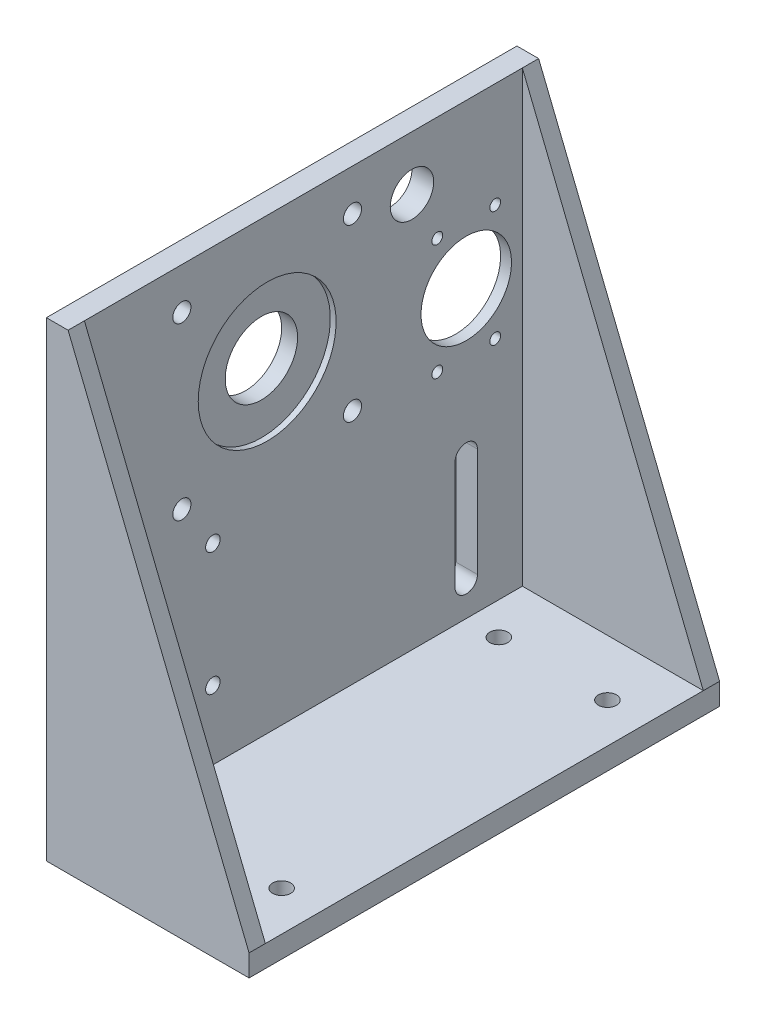
SolidWorks part; units mm, degrees
material "AISI 304"
ref_plane "Front" through (0, 0, 0) normal (0, 0, 1) x (1, 0, 0)
ref_plane "Top" through (0, 0, 0) normal (0, 1, 0) x (1, 0, 0)
ref_plane "Right" through (0, 0, 0) normal (1, 0, 0) x (0, 0, -1)
sketch "Sketch1" plane through (0, 0, 0) normal (1, 0, 0) x (0, 0, -1)
  line L1 (0, 0) -> (130, 0)
  line L2 (0, 0) -> (0, 130)
  line L3 (0, 130) -> (130, 130)
  line L4 (130, 0) -> (130, 130)
  dimension "D1" = 130
  dimension "D2" = 130
extrude "Boss-Extrude1" add sketch "Sketch1" along normal blind 6
sketch "Sketch2" plane through (6, 0, 0) normal (1, 0, 0) x (0, 0, -1)
  line L0 (130, 0) -> (130, 130) construction
  line L1 (0, 0) -> (130, 0)
  line L2 (0, 0) -> (0, 6)
  line L3 (0, 6) -> (130, 6)
  line L4 (130, 0) -> (130, 6)
  dimension "D1" = 6
extrude "Boss-Extrude2" add sketch "Sketch2" along normal blind 50
sketch "Sketch3" plane through (0, 0, -130) normal (0, 0, -1) x (-1, 0, 0)
  line L0 (-6, 130) -> (-56, 6)
  line L1 (-6, 6) -> (-6, 130) construction
  line L2 (-56, 6) -> (-6, 6) construction
  line L3 (-6, 6) -> (-6, 130)
  line L4 (-56, 6) -> (-6, 6)
extrude "Boss-Extrude3" add sketch "Sketch3" against normal blind 4.5
sketch "Sketch4" plane through (0, 0, 0) normal (0, 0, 1) x (1, 0, 0)
  line L0 (6, 130) -> (56, 6)
  line L1 (56, 6) -> (6, 6) construction
  line L2 (6, 130) -> (6, 6) construction
  line L3 (56, 6) -> (6, 6)
  line L4 (6, 130) -> (6, 6)
extrude "Boss-Extrude4" add sketch "Sketch4" against normal blind 4.5
sketch "Sketch5" plane through (6, 0, 0) normal (-1, 0, 0) x (0, 0, 1)
  line L0 (-130, 0) -> (-130, 130) construction
  line L2 (0, 0) -> (-130, 0) construction
  circle A0 centre (-55, 95) radius 19.05
  dimension "D2" = 95
  dimension "D3" = 38.1
  dimension "D4" = 75
extrude "Cut-Extrude1" cut sketch "Sketch5" along normal blind 1.6
sketch "Sketch6" plane through (4.4, 0, 0) normal (1, 0, 0) x (0, 0, -1)
  circle A0 centre (55, 95) radius 10
  dimension "D1" = 20
extrude "Cut-Extrude2" cut sketch "Sketch6" against normal through all
sketch "Sketch7" plane through (0, 0, 0) normal (-1, 0, 0) x (0, 0, 1)
  line L0 (-78.57, 118.57) -> (-31.43, 71.43) construction
  line L5 (-78.57, 118.57) -> (-31.43, 118.57) construction
  line L6 (-78.57, 118.57) -> (-78.57, 71.43) construction
  line L7 (-78.57, 71.43) -> (-31.43, 71.43) construction
  line L8 (-31.43, 118.57) -> (-31.43, 71.43) construction
  circle A0 centre (-55, 95) radius 10 construction
  circle A1 centre (-78.57, 118.57) radius 2.5
  circle A2 centre (-31.43, 118.57) radius 2.5
  circle A3 centre (-31.43, 71.43) radius 2.5
  circle A4 centre (-78.57, 71.43) radius 2.5
  point P4 (-55, 95)
  dimension "D2" = 5
  dimension "D1" = 47.14
extrude "Cut-Extrude3" cut sketch "Sketch7" against normal through all
sketch "Sketch8" plane through (0, 0, 0) normal (-1, 0, 0) x (0, 0, 1)
  line L1 (0, 0) -> (-130, 0) construction
  line L2 (-118, 101) -> (-102, 69) construction
  line L3 (-118, 101) -> (-102, 101) construction
  line L4 (-118, 101) -> (-118, 69) construction
  line L5 (-118, 69) -> (-102, 69) construction
  line L6 (-102, 101) -> (-102, 69) construction
  circle A0 centre (-110, 85) radius 12.5
  circle A1 centre (-118, 101) radius 1.5
  circle A2 centre (-102, 101) radius 1.5
  circle A3 centre (-102, 69) radius 1.5
  circle A4 centre (-118, 69) radius 1.5
  circle A5 centre (-55, 95) radius 10 construction
  point P10 (-110, 85)
  dimension "D1" = 25
  dimension "D6" = 3
  dimension "D5" = 8
  dimension "D7" = 55
  dimension "D3" = 85
  dimension "D4" = 16
extrude "Encoder mounting" cut sketch "Sketch8" against normal through all
sketch "Sketch9" plane through (0, 0, 0) normal (-1, 0, 0) x (0, 0, 1)
  line L0 (-130, 0) -> (-130, 130) construction
  line L1 (-130, 104) -> (-95, 104)
  line L2 (-130, 104) -> (-130, 66)
  line L3 (-130, 66) -> (-95, 66)
  line L4 (-95, 104) -> (-95, 66)
  line L5 (-95, 85) -> (-110, 85) construction
  circle A0 centre (-110, 85) radius 12.5 construction
  point P4 (-110, 85)
  dimension "D2" = 38
  dimension "D3" = 15
extrude "Sqr Slot fro encoder" cut sketch "Sketch9" against normal blind 3
sketch "Sketch10" plane through (0, 0, 0) normal (-1, 0, 0) x (0, 0, 1)
  circle A0 centre (-95, 115) radius 6
  circle A1 centre (-55, 95) radius 10 construction
  dimension "D1" = 40
  dimension "D2" = 20
  dimension "D3" = 12
extrude "Cut-Extrude6" cut sketch "Sketch10" against normal through all
sketch "Sketch11" plane through (0, 0, 0) normal (-1, 0, 0) x (0, 0, 1)
  line L0 (0, 130) -> (0, 0) construction
  circle A0 centre (-102, 47) radius 4
  circle A1 centre (-110, 85) radius 12.5 construction
  dimension "D1" = 102
  dimension "D3" = 8
  dimension "D4" = 38
extrude "Cut-Extrude7" [suppressed] cut sketch "Sketch11" against normal through all
sketch "Sketch12" plane through (0, 0, 0) normal (-1, 0, 0) x (0, 0, 1)
  line L0 (0, 0) -> (-130, 0) construction
  line L1 (0, 130) -> (0, 0) construction
  line L2 (-10, 25) -> (-40, 25) construction
  line L3 (-10, 25) -> (-10, 59) construction
  line L4 (-10, 59) -> (-40, 59) construction
  line L5 (-40, 25) -> (-40, 59) construction
  circle A0 centre (-10, 25) radius 2
  circle A1 centre (-10, 59) radius 2
  circle A2 centre (-40, 59) radius 2
  circle A3 centre (-40, 25) radius 2
  dimension "D1" = 4
  dimension "D2" = 34
  dimension "D3" = 25
  dimension "D4" = 30
  dimension "D5" = 10
extrude "Cut-Extrude8" cut sketch "Sketch12" against normal through all
sketch "Sketch13" plane through (0, 0, 0) normal (-1, 0, 0) x (0, 0, 1)
  line L0 (-60, 12) -> (-30, 12) construction
  line L1 (-60, 13.5) -> (-30, 13.5)
  line L2 (-60, 10.5) -> (-30, 10.5)
  line L3 (0, 0) -> (-130, 0) construction
  line L4 (0, 130) -> (0, 0) construction
  arc A0 (-60, 13.5) -> (-60, 10.5) centre (-60, 12) ccw
  arc A1 (-30, 10.5) -> (-30, 13.5) centre (-30, 12) ccw
  point P2 (-45, 12)
  dimension "D4" = 30
  dimension "D1" = 12
  dimension "D2" = 3
  dimension "D3" = 30
extrude "Cut-Extrude9" [suppressed] cut sketch "Sketch13" against normal through all
chamfer "Chamfer1" distance 2.5 angle 45 4 edges at (0, 71.43, -28.93) (0, 71.43, -76.07) (0, 118.57, -28.93) (0, 118.57, -76.07)
sketch "Sketch14" plane through (0, 0, 0) normal (0, -1, 0) x (1, 0, 0)
  line L0 (0, 0) -> (0, -130) construction
  line L1 (15, -20) -> (45, -20) construction
  line L2 (15, -20) -> (15, -110) construction
  line L3 (15, -110) -> (45, -110) construction
  line L4 (45, -20) -> (45, -110) construction
  line L6 (56, 0) -> (0, 0) construction
  line L7 (56, -130) -> (0, -130) construction
  circle A0 centre (15, -20) radius 2.5
  circle A1 centre (45, -20) radius 2.5
  circle A2 centre (15, -110) radius 2.5
  circle A3 centre (45, -110) radius 2.5
  dimension "D5" = 5
  dimension "D1" = 15
  dimension "D3" = 20
  dimension "D4" = 20
  dimension "D6" = 30
extrude "Cut-Extrude10" cut sketch "Sketch14" against normal through all
sketch "Sketch15" plane through (0, 0, 0) normal (-1, 0, 0) x (0, 0, 1)
  line L0 (-110, 15) -> (-110, 45) construction
  line L1 (-113.1, 15) -> (-113.1, 45)
  line L2 (-106.9, 15) -> (-106.9, 45)
  line L3 (-110, 85) -> (-110, 45) construction
  arc A0 (-113.1, 15) -> (-106.9, 15) centre (-110, 15) ccw
  arc A1 (-106.9, 45) -> (-113.1, 45) centre (-110, 45) ccw
  circle A2 centre (-110, 85) radius 12.5 construction
  point P2 (-110, 30)
  dimension "D1" = 3.1
  dimension "D3" = 40
  dimension "D2" = 30
extrude "Cut-Extrude11" cut sketch "Sketch15" against normal through all
